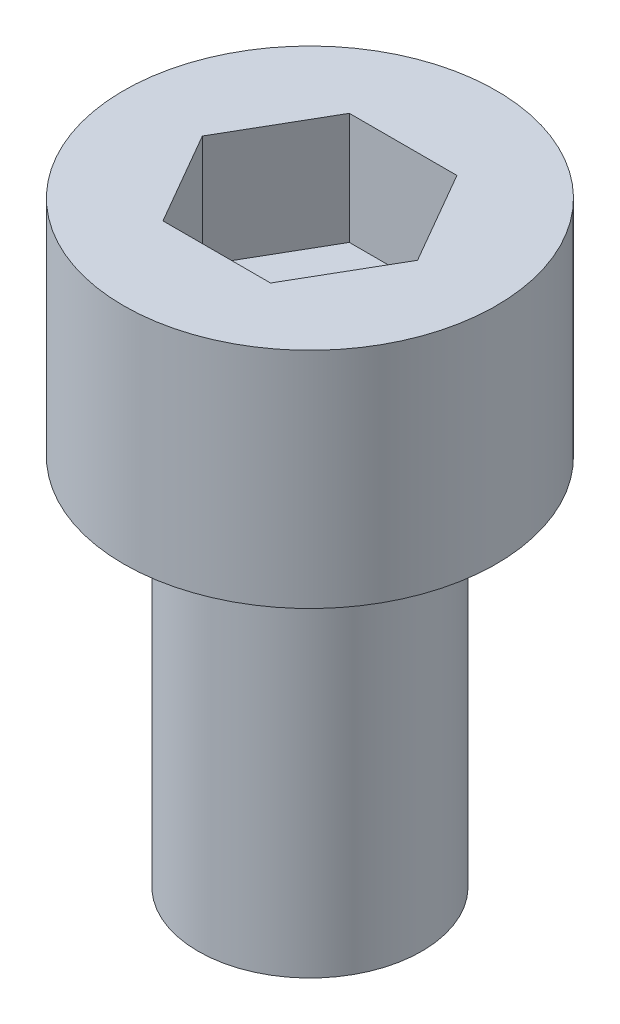
SolidWorks part; units mm, degrees
material "AISI 304"
ref_plane "Front Plane" through (0, 0, 0) normal (0, 0, 1) x (1, 0, 0)
ref_plane "Top Plane" through (0, 0, 0) normal (0, 1, 0) x (1, 0, 0)
ref_plane "Right Plane" through (0, 0, 0) normal (1, 0, 0) x (0, 0, -1)
sketch "Sketch1" plane through (0, 0, 0) normal (0, 0, 1) x (1, 0, 0)
  line L0 (0, 61.6916) -> (0, -59.3578) construction
  line L1 (0, -10) -> (3, -10)
  line L2 (3, -10) -> (3, 0)
  line L3 (3, 0) -> (5, 0)
  line L4 (5, 0) -> (5, 6)
  line L5 (5, 6) -> (0, 6)
  line L6 (0, 6) -> (0, -10)
  dimension "D1" = 10
  dimension "D2" = 10
  dimension "D3" = 6
  dimension "D4" = 6
revolve "Revolve1" add sketch "Sketch1" angle 360 about L0
sketch "Sketch2" plane through (0, 6, 0) normal (0, 1, 0) x (-1, 0, 0)
  line L1 (-1.4434, -2.5) -> (1.4434, -2.5)
  line L2 (1.4434, -2.5) -> (2.8868, 0)
  line L3 (2.8868, 0) -> (1.4434, 2.5)
  line L4 (1.4434, 2.5) -> (-1.4434, 2.5)
  line L5 (-1.4434, 2.5) -> (-2.8868, 0)
  line L6 (-2.8868, 0) -> (-1.4434, -2.5)
  circle A0 centre (0, 0) radius 2.5 construction
  dimension "D1" = 5
extrude "Cut-Extrude1" cut sketch "Sketch2" against normal blind 3
